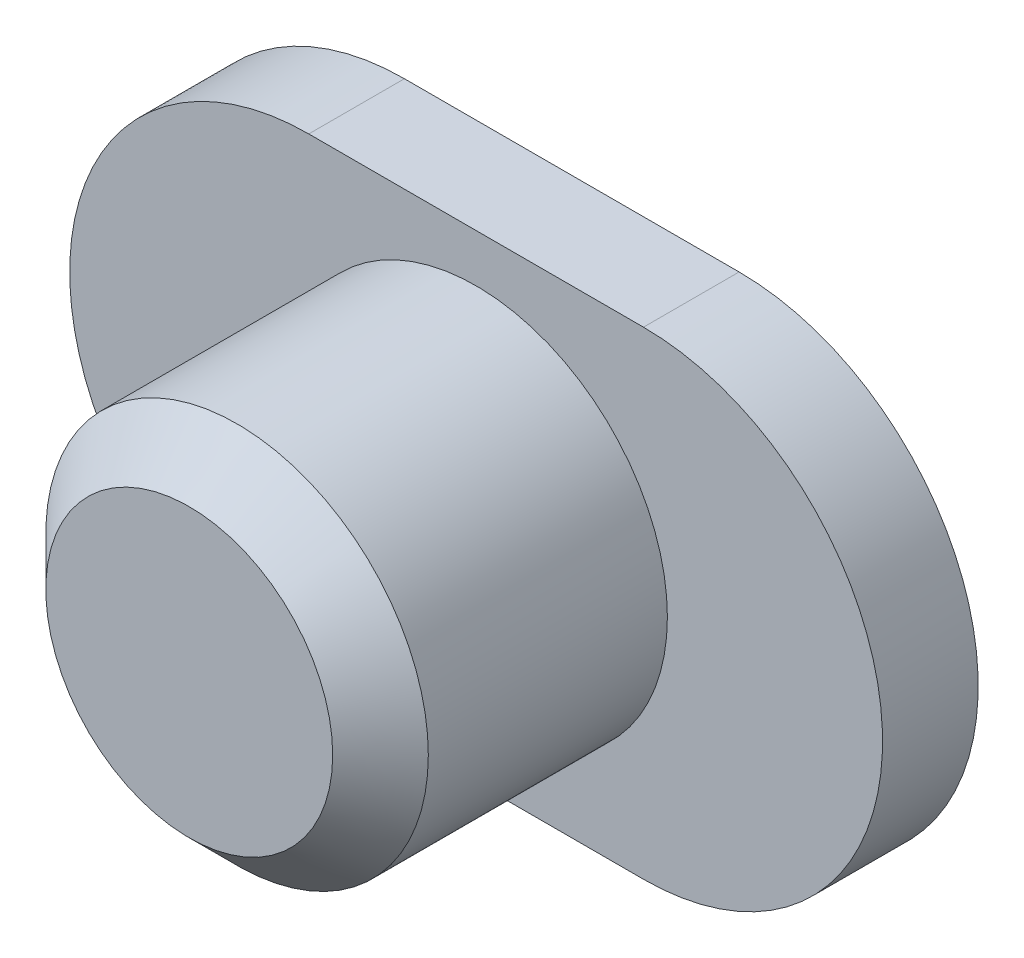
SolidWorks part; units mm, degrees
material "Латунь"
ref_plane "Спереди" through (0, 0, 0) normal (0, 0, 1) x (1, 0, 0)
ref_plane "Сверху" through (0, 0, 0) normal (0, 1, 0) x (1, 0, 0)
ref_plane "Справа" through (0, 0, 0) normal (1, 0, 0) x (0, 0, -1)
sketch "Эскиз1" plane through (0, 0, 0) normal (0, 0, 1) x (1, 0, 0)
  line L0 (-3.5, 0) -> (3.5, 0) construction
  line L1 (-3.5, 5) -> (3.5, 5)
  line L2 (-3.5, -5) -> (3.5, -5)
  arc A0 (-3.5, 5) -> (-3.5, -5) centre (-3.5, 0) ccw
  arc A1 (3.5, -5) -> (3.5, 5) centre (3.5, 0) ccw
  point P2 (0, 0)
  dimension "D1" = 5
  dimension "D2" = 7
extrude "Бобышка-Вытянуть1" add sketch "Эскиз1" along normal blind 2
sketch "Эскиз2" plane through (0, 0, 2) normal (0, 0, 1) x (1, 0, 0)
  circle A0 centre (0, 0) radius 4
  dimension "D1" = 8
extrude "Бобышка-Вытянуть2" add sketch "Эскиз2" along normal blind 6
sketch "Эскиз3" plane through (0, 0, 0) normal (0, 0, -1) x (-1, 0, 0)
  circle A0 centre (0, 0) radius 3
  dimension "D1" = 6
extrude "Вырез-Вытянуть1" cut sketch "Эскиз3" against normal blind 4
chamfer "Фаска1" distance 1 angle 45 1 edges at (4, 0, 8)
